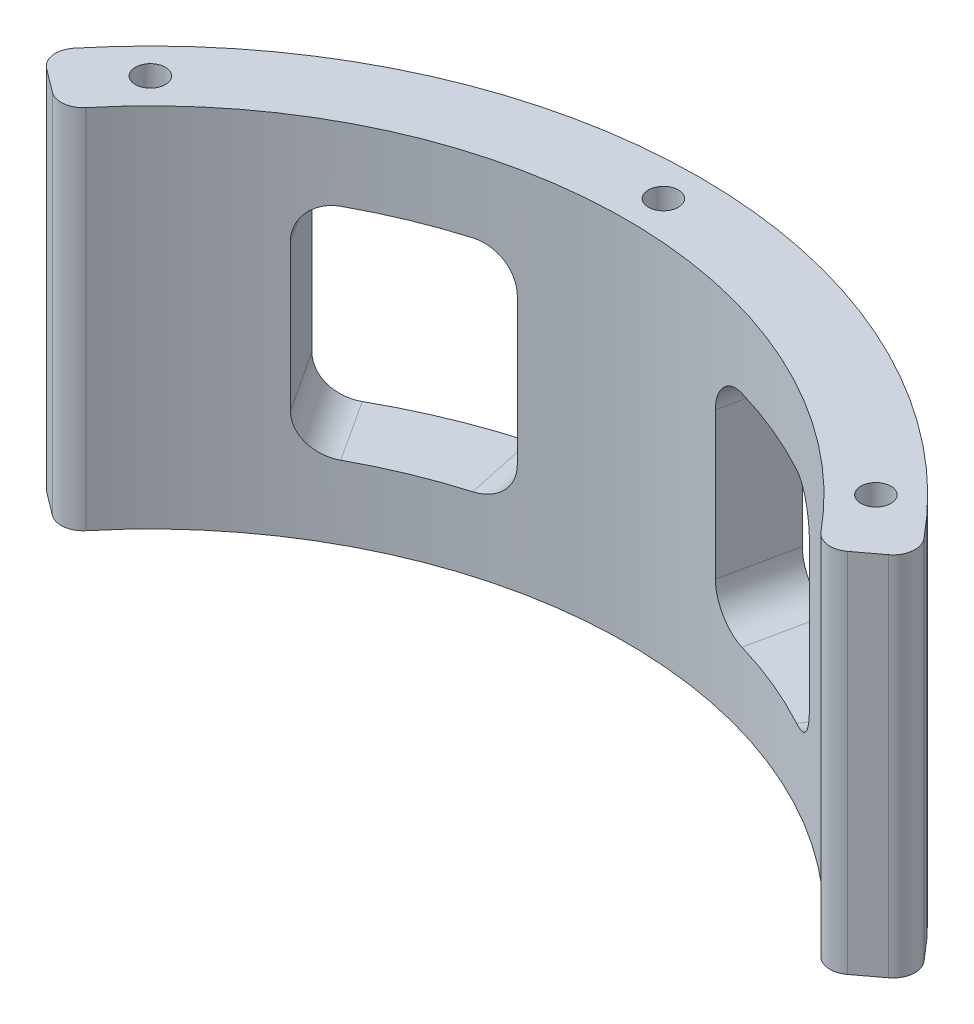
SolidWorks part; units mm, degrees
ref_plane "前视基准面" through (0, 0, 0) normal (0, 0, 1) x (1, 0, 0)
ref_plane "上视基准面" through (0, 0, 0) normal (0, 1, 0) x (1, 0, 0)
ref_plane "右视基准面" through (0, 0, 0) normal (1, 0, 0) x (0, 0, -1)
sketch "草图1" plane through (0, 0, 0) normal (0, 1, 0) x (1, 0, 0)
  line L0 (0, 0) -> (0, 81.5111) construction
  line L1 (0, 0) -> (-49.4975, 49.4975) construction
  line L2 (0, 0) -> (-59.8977, 45.1361)
  line L3 (0, 0) -> (59.8977, 45.1361)
  arc A6 (23.6017, -44.079) -> (26.3727, -42.4792) centre (0, 0) ccw construction
  arc A8 (49.9744, 1.5998) -> (49.9744, -1.5998) centre (50, 0) ccw
  circle A9 centre (25, -43.3013) radius 1.6
  arc A21 (55.9045, 42.1271) -> (-55.9045, 42.1271) centre (0, 0) ccw construction
  circle A22 centre (0, 70) radius 2.05
  circle A23 centre (-49.4975, 49.4975) radius 2.05
  circle A24 centre (49.4975, 49.4975) radius 2.05
  arc A25 (59.8977, 45.1361) -> (-59.8977, 45.1361) centre (0, 0) ccw
  arc A26 (49.9744, -1.5998) -> (49.9744, 1.5998) centre (0, 0) ccw construction
  arc A29 (51.9113, 39.118) -> (-51.9113, 39.118) centre (0, 0) ccw
  dimension "D2" = 70
  dimension "D3" = 65
  dimension "D4" = 4.1
  dimension "D6" = 75
  dimension "D5" = 45
  dimension "D11" = 8
extrude "凸台-拉伸1" add sketch "草图1" along normal mid plane 50
fillet "圆角2" radius 3 4 edges at (59.8977, 0, -45.1361) (51.9113, 0, -39.118) (-59.8977, 0, -45.1361) (-51.9113, 0, -39.118)
sketch "草图2" plane through (0, 0, 0) normal (0, 1, 0) x (1, 0, 0)
  line L0 (0, 0) -> (-40.8479, 62.9003)
  line L1 (0, 0) -> (0, 70) construction
  line L2 (0, 0) -> (40.8479, 62.9003)
  line L3 (0, 0) -> (-15.5934, 73.3611)
  line L4 (0, 0) -> (15.5934, 73.3611)
  line L5 (0, 0) -> (-36.9666, 89.2452) construction
  arc A0 (57.965, 47.5927) -> (-57.965, 47.5927) centre (0, 0) ccw construction
  circle A1 centre (0, 70) radius 2.05 construction
  circle A2 centre (-49.4975, 49.4975) radius 2.05 construction
  arc A3 (50.135, 41.3701) -> (-50.135, 41.3701) centre (0, 0) ccw construction
  arc A4 (57.965, 47.5927) -> (-57.965, 47.5927) centre (0, 0) ccw
  arc A5 (50.135, 41.3701) -> (-50.135, 41.3701) centre (0, 0) ccw
  dimension "D1" = 21
extrude "切除-拉伸1" cut sketch "草图2" against normal mid plane 30 contours A5 L3 A4 L0 | A5 L2 A4 L4
fillet "圆角3" radius 5 8 edges at (38.1247, -15, -58.7069) (14.5538, -15, -68.4703) (14.5538, 15, -68.4703) (38.1247, 15, -58.7069) (-14.5538, 15, -68.4703) (-38.1247, 15, -58.7069) (-38.1247, -15, -58.7069) (-14.5538, -15, -68.4703)
